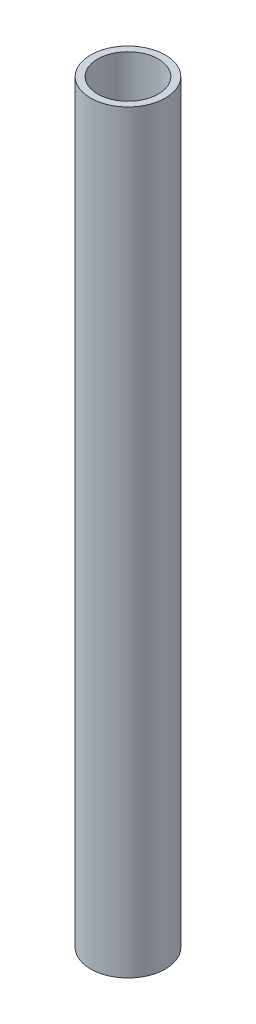
SolidWorks part; units mm, degrees
material "СТ3КП"
ref_plane "Спереди" through (0, 0, 0) normal (0, 0, 1) x (1, 0, 0)
ref_plane "Сверху" through (0, 0, 0) normal (0, 1, 0) x (1, 0, 0)
ref_plane "Справа" through (0, 0, 0) normal (1, 0, 0) x (0, 0, -1)
sketch "Эскиз1" plane through (0, 0, 0) normal (0, 1, 0) x (1, 0, 0)
  line L0 (0, 200864.2922) -> (0, -249057.8193) construction
  line L1 (-130, 9.15) -> (130, 9.15) construction
  circle B0 centre (0, -1.5) radius 8.65
  circle B1 centre (0, -1.5) radius 10.65
sketch_block_instance "Труба 21_3х2 1_2-1"
sketch_block "Труба 21_3х2 1_2" parameters "D2"=21.3, "D1"=2
extrude "Бобышка-Вытянуть1" add sketch "Эскиз1" along normal up to vertex (215 mm away)
